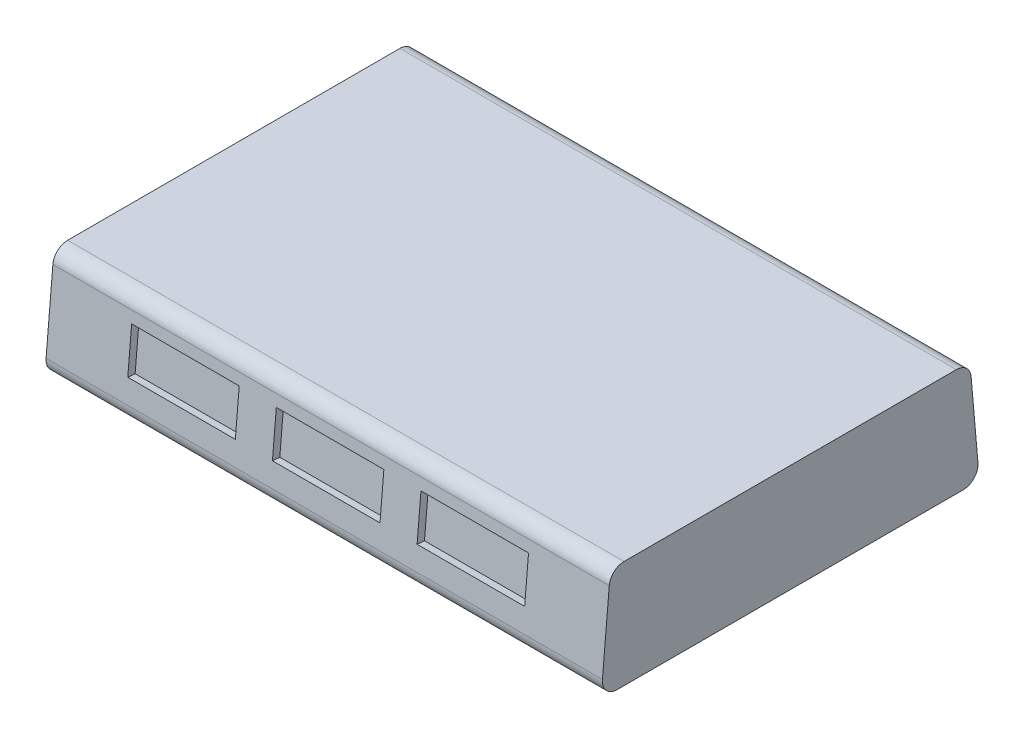
SolidWorks part; units mm, degrees
ref_plane "Front Plane" through (0, 0, 0) normal (0, 0, 1) x (1, 0, 0)
ref_plane "Top Plane" through (0, 0, 0) normal (0, 1, 0) x (1, 0, 0)
ref_plane "Right Plane" through (0, 0, 0) normal (1, 0, 0) x (0, 0, -1)
sketch "Sketch1" plane through (0, 0, 0) normal (1, 0, 0) x (0, 0, -1)
  line L0 (-24.3911, 5.4243) -> (-25.3098, -5.0757)
  line L1 (-23.3174, -7.25) -> (23.3174, -7.25)
  line L2 (25.3098, -5.0757) -> (24.3911, 5.4243)
  line L3 (22.3988, 7.25) -> (-22.3988, 7.25)
  line L4 (0, -7.25) -> (0, 7.25) construction
  arc A0 (24.3911, 5.4243) -> (22.3988, 7.25) centre (22.3988, 5.25) ccw
  arc A1 (23.3174, -7.25) -> (25.3098, -5.0757) centre (23.3174, -5.25) ccw
  arc A2 (-25.3098, -5.0757) -> (-23.3174, -7.25) centre (-23.3174, -5.25) ccw
  arc A3 (-24.3911, 5.4243) -> (-22.3988, 7.25) centre (-22.3988, 5.25) cw
  point P12 (25.5, -7.25)
  point P15 (-25.5, -7.25)
  dimension "D4" = 2
  dimension "D1" = 51
  dimension "D2" = 14.5
  dimension "D3" = 5
extrude "Boss-Extrude1" add sketch "Sketch1" along normal mid plane 75
sketch "Sketch2" plane through (0, 2.1589, 24.6768) normal (0, 0.0872, 0.9962) x (1, 0, 0)
  line L0 (0, -4.2222) -> (0, 1.7778) construction
  line L1 (-26.75, 1.7778) -> (-12.25, 1.7778)
  line L2 (-26.75, 1.7778) -> (-26.75, -4.2222)
  line L3 (-26.75, -4.2222) -> (-12.25, -4.2222)
  line L4 (-12.25, 1.7778) -> (-12.25, -4.2222)
  line L5 (-7.25, 1.7778) -> (7.25, 1.7778)
  line L6 (-7.25, 1.7778) -> (-7.25, -4.2222)
  line L7 (-7.25, -4.2222) -> (7.25, -4.2222)
  line L8 (7.25, 1.7778) -> (7.25, -4.2222)
  line L9 (12.25, 1.7778) -> (26.75, 1.7778)
  line L10 (12.25, 1.7778) -> (12.25, -4.2222)
  line L11 (12.25, -4.2222) -> (26.75, -4.2222)
  line L12 (26.75, 1.7778) -> (26.75, -4.2222)
  line L13 (37.5, 3.2778) -> (-37.5, 3.2778) construction
  line L14 (0, 1.7778) -> (0, 3.2778) construction
  line L15 (-12.25, -4.2222) -> (-7.25, -4.2222) construction
  line L16 (7.25, -4.2222) -> (12.25, -4.2222) construction
  dimension "D1" = 6
  dimension "D2" = 14.5
  dimension "D3" = 5
  dimension "D4" = 1.5
extrude "Cut-Extrude1" cut sketch "Sketch2" against normal blind 1
sketch "Sketch3" plane through (0, 2.1589, -24.6768) normal (0, 0.0872, -0.9962) x (-1, 0, 0)
  line L0 (-8.5, 3.2778) -> (-8.5, 1.5078) construction
  line L1 (11.75, -1.2222) -> (26.75, -1.2222)
  line L2 (11.75, -1.2222) -> (11.75, -3.2222)
  line L3 (11.75, -3.2222) -> (26.75, -3.2222)
  line L4 (26.75, -1.2222) -> (26.75, -3.2222)
  line L5 (-17.5, 1.5078) -> (-8.5, 1.5078)
  line L6 (-17.5, 1.5078) -> (-17.5, -5.4922)
  line L7 (-17.5, -5.4922) -> (-8.5, -5.4922)
  line L8 (-8.5, 1.5078) -> (-8.5, -5.4922)
  line L9 (-37.5, 3.2778) -> (37.5, 3.2778) construction
  line L10 (-8.5, -5.4922) -> (-8.5, -7.2623) construction
  line L11 (-37.5, -7.2623) -> (37.5, -7.2623) construction
  line L12 (-37.5, -7.2623) -> (-37.5, 3.2778) construction
  line L14 (26.75, 6.0523) -> (26.75, 0.1434) construction
  line L15 (26.75, 6.0523) -> (26.75, 0.1434) construction
  dimension "D1" = 9
  dimension "D2" = 7
  dimension "D3" = 15
  dimension "D4" = 2
  dimension "D5" = 20
  dimension "D7" = 4.5
extrude "Cut-Extrude2" cut sketch "Sketch3" against normal blind 1
